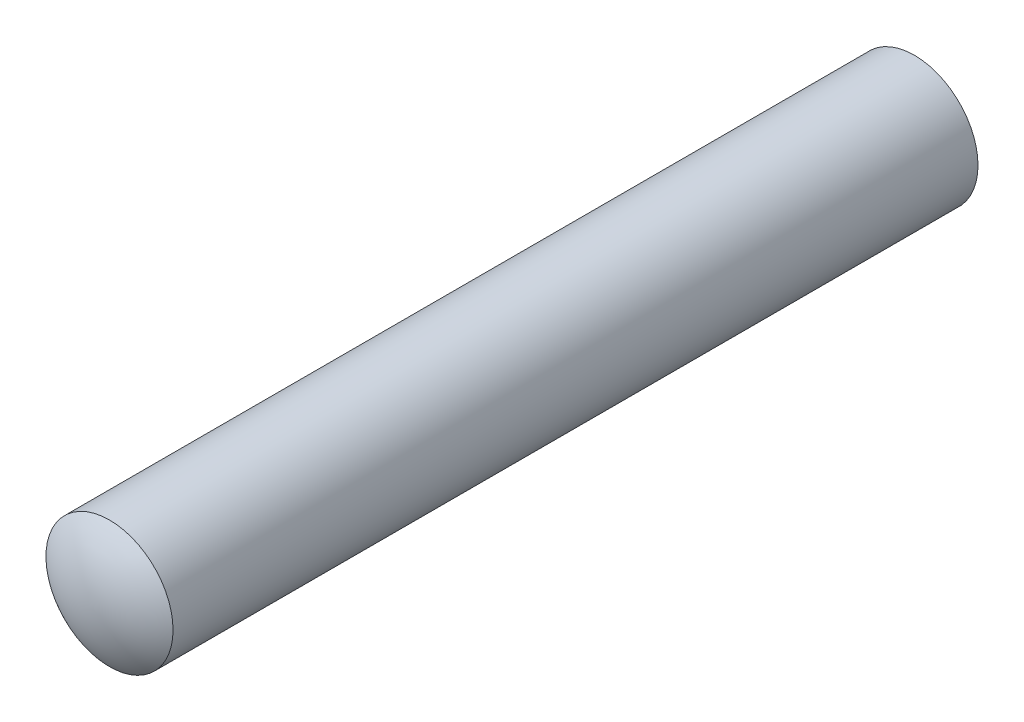
SolidWorks part; units mm, degrees
ref_plane "前基準面" through (0, 0, 0) normal (0, 0, 1) x (1, 0, 0)
ref_plane "上基準面" through (0, 0, 0) normal (0, 1, 0) x (1, 0, 0)
ref_plane "右基準面" through (0, 0, 0) normal (1, 0, 0) x (0, 0, -1)
sketch "草圖1" plane through (0, 0, 0) normal (1, 0, 0) x (0, 0, -1)
  line L0 (-10, 0) -> (25.875, 0) construction
  line L1 (-9.5, 1.5) -> (9.5, 1.5)
  line L2 (-10, 0) -> (10, 0)
  arc A0 (-10, 0) -> (-9.5, 1.5) centre (-7.5, 0) cw
  arc A1 (9.5, 1.5) -> (10, 0) centre (7.5, 0) cw
  dimension "D1" = 20
  dimension "D2" = 3
  dimension "D3" = 0.5
  dimension "D4" = 0.5
revolve "旋轉1" add sketch "草圖1" angle 360 about L0
